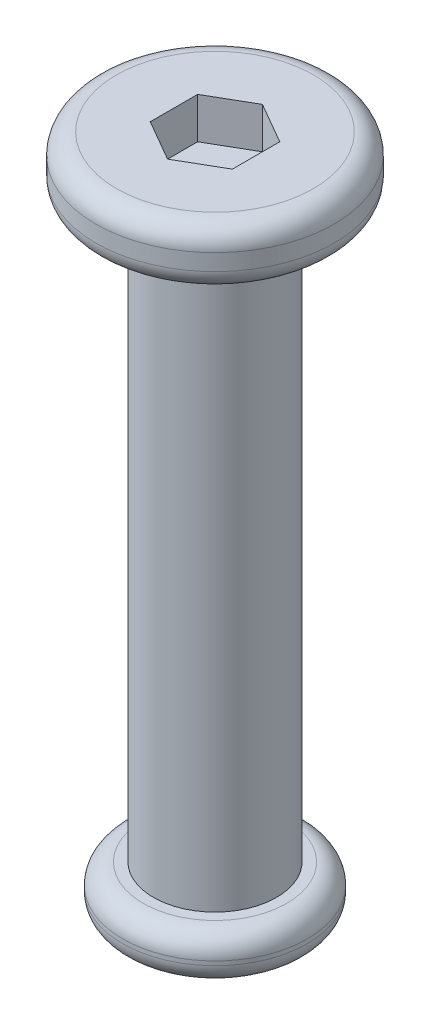
SolidWorks part; units mm, degrees
material "AISI 304"
ref_plane "前视基准面" through (0, 0, 0) normal (0, 0, 1) x (1, 0, 0)
ref_plane "上视基准面" through (0, 0, 0) normal (0, 1, 0) x (1, 0, 0)
ref_plane "右视基准面" through (0, 0, 0) normal (1, 0, 0) x (0, 0, -1)
other "Configuration Table"
sketch "草图1" plane through (0, 0, 0) normal (0, 1, 0) x (1, 0, 0)
  circle A0 centre (0, 0) radius 2.9
  dimension "D1" = 5.8
extrude "凸台-拉伸1" add sketch "草图1" along normal blind 1.4
sketch "草图2" plane through (0, 1.4, 0) normal (0, 1, 0) x (1, 0, 0)
  line L0 (0, 0) -> (0, 3.5021) construction
  line L1 (1, 0.5774) -> (0, 1.1547)
  line L2 (0, 1.1547) -> (-1, 0.5774)
  line L3 (-1, 0.5774) -> (-1, -0.5774)
  line L4 (-1, -0.5774) -> (0, -1.1547)
  line L5 (0, -1.1547) -> (1, -0.5774)
  line L6 (1, -0.5774) -> (1, 0.5774)
  circle A0 centre (0, 0) radius 1 construction
  dimension "D1" = 2
extrude "切除-拉伸1" cut sketch "草图2" against normal blind 1
sketch "草图3" plane through (0, 0, 0) normal (0, -1, 0) x (1, 0, 0)
  circle A0 centre (0, 0) radius 1.5
  dimension "D1" = 3
extrude "凸台-拉伸2" add sketch "草图3" along normal blind 14
sketch "草图4" plane through (0, -14, 0) normal (0, -1, 0) x (1, 0, 0)
  circle A0 centre (0, 0) radius 2.25
  dimension "D1" = 4.5
extrude "凸台-拉伸3" add sketch "草图4" along normal blind 1.1
sketch "草图5" plane through (0, -15.1, 0) normal (0, -1, 0) x (1, 0, 0)
  line L0 (0, 0) -> (0, 2.5586) construction
  line L1 (0.65, 0.3753) -> (0, 0.7506)
  line L2 (0, 0.7506) -> (-0.65, 0.3753)
  line L3 (-0.65, 0.3753) -> (-0.65, -0.3753)
  line L4 (-0.65, -0.3753) -> (0, -0.7506)
  line L5 (0, -0.7506) -> (0.65, -0.3753)
  line L6 (0.65, -0.3753) -> (0.65, 0.3753)
  circle A0 centre (0, 0) radius 0.65 construction
  dimension "D1" = 1.3
extrude "切除-拉伸2" cut sketch "草图5" against normal blind 0.8
fillet "圆角1" radius 0.5 4 edges at (0, 1.4, 2.9) (0, 0, 2.9) (0, -14, -2.25) (0, -15.1, -2.25)
